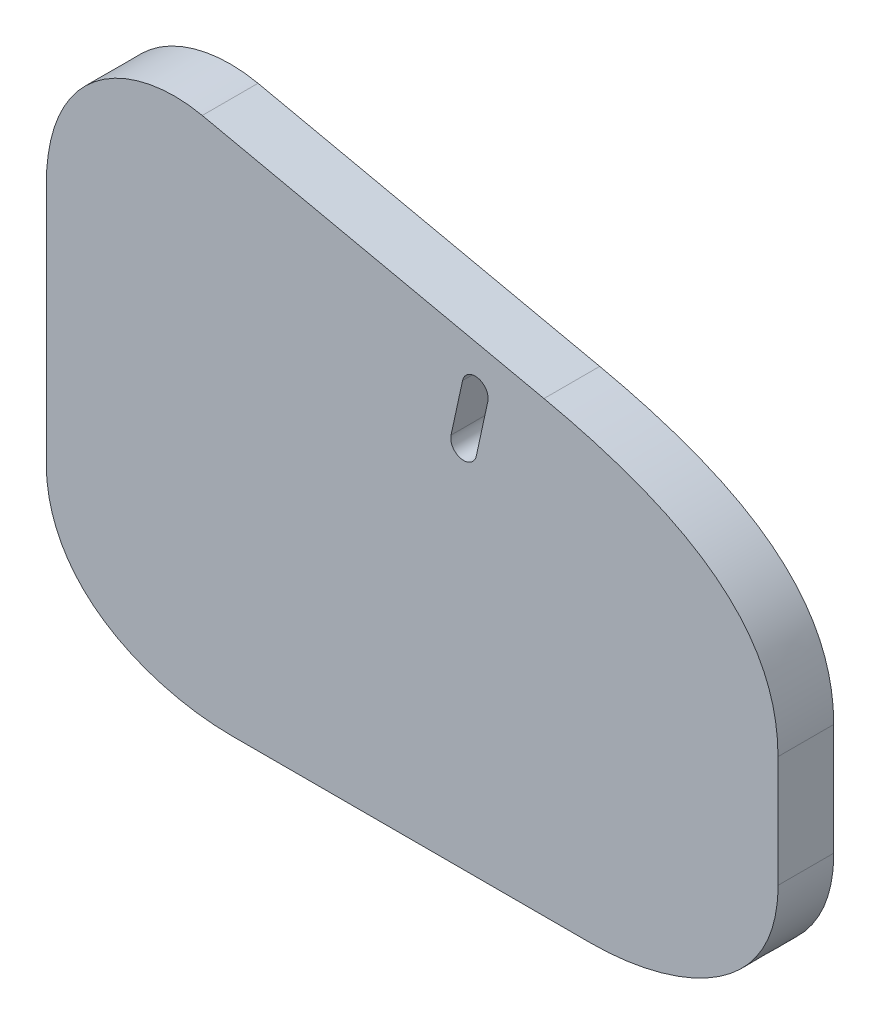
SolidWorks part; units mm, degrees
ref_plane "Спереди" through (0, 0, 0) normal (0, 0, 1) x (1, 0, 0)
ref_plane "Сверху" through (0, 0, 0) normal (0, 1, 0) x (1, 0, 0)
ref_plane "Справа" through (0, 0, 0) normal (1, 0, 0) x (0, 0, -1)
sketch "Эскиз1_fr" plane through (0, 0, 0) normal (0, 0, 1) x (1, 0, 0)
  line L0 (0, 0) -> (0, 20)
  line L1 (-41.9869, 54.6497) -> (-103.3012, 67.9789)
  line L2 (-131.2925, 43.0977) -> (-131.2925, 0)
  line L3 (-33.5451, -25.7698) -> (-97.9695, -25.7698)
  line L4 (-54.3328, 49.6459) -> (-56.3993, 40.1399)
  line L5 (-54.3328, 49.6459) -> (-56.3993, 40.1399) construction
  line L6 (-52.0671, 49.1533) -> (-54.1336, 39.6474)
  line L7 (-56.5986, 50.1384) -> (-58.6651, 40.6325)
  arc A0 (-52.0671, 49.1533) -> (-56.5986, 50.1384) centre (-54.3328, 49.6459) ccw
  arc A1 (-58.6651, 40.6325) -> (-54.1336, 39.6474) centre (-56.3993, 40.1399) ccw
  spline S0 degree 3 poles (0, 20) (0, 38.146) (-14.2095, 48.6111) (-41.9869, 54.6497) knots 0 0 0 0 1 1 1 1
  spline S1 degree 3 poles (-103.3012, 67.9789) (-115.5, 70.6308) (-131.2925, 63.3933) (-131.2925, 43.0977) knots 0 0 0 0 1 1 1 1
  spline S2 degree 3 poles (-33.5451, -25.7698) (-19.4449, -25.7698) (0, -19.0638) (0, 0) knots 0 0 0 0 1 1 1 1
  spline S3 degree 3 poles (-97.9695, -25.7698) (-112.0112, -25.7698) (-131.2925, -19.0252) (-131.2925, 0) knots 0 0 0 0 1 1 1 1
  point P11 (-55.3661, 44.8929)
  dimension "D1" = 20
extrude "Бобышка-Вытянуть1" add sketch "Эскиз1_fr" along normal blind 10 contours S3 L3 S2 L0 S0 L1 S1 L2 A1 L7 A0 L6
curve "Объединенная кривая1"
